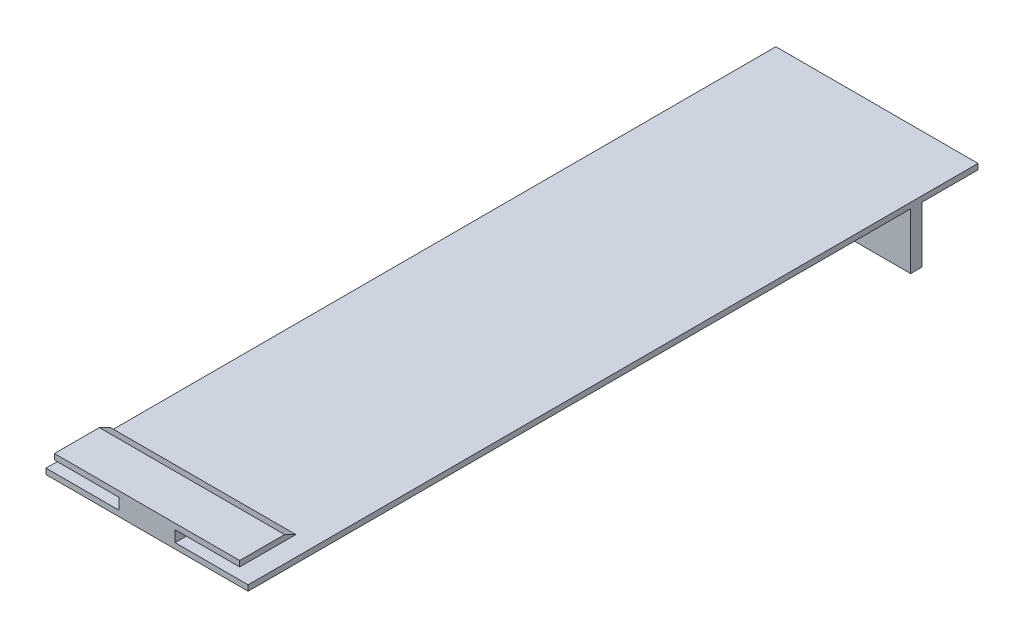
SolidWorks part; units mm, degrees
ref_plane "Front Plane" through (0, 0, 0) normal (0, 0, 1) x (1, 0, 0)
ref_plane "Top Plane" through (0, 0, 0) normal (0, 1, 0) x (1, 0, 0)
ref_plane "Right Plane" through (0, 0, 0) normal (1, 0, 0) x (0, 0, -1)
sketch "Sketch1" plane through (0, 0, 0) normal (0, 0, 1) x (1, 0, 0)
  line L1 (-18, -0.5) -> (18, -0.5)
  line L2 (-18, -0.5) -> (-18, 0.5)
  line L3 (-18, 0.5) -> (18, 0.5)
  line L4 (18, -0.5) -> (18, 0.5)
  line L5 (-18, -0.5) -> (18, 0.5) construction
  line L6 (-18, 0.5) -> (18, -0.5) construction
  point P0 (0, 0)
  dimension "D1" = 1
  dimension "D2" = 36
extrude "Boss-Extrude1" add sketch "Sketch1" along normal mid plane 130
ref_plane "Plane1" through (0, 0, 60) normal (0, 0, 1) x (1, 0, 0)
sketch "Sketch2" plane through (0, 0, 60) normal (0, 0, 1) x (1, 0, 0)
  line L0 (-5, 0.5) -> (-5, 2.5)
  line L1 (18, 0.5) -> (-18, 0.5) construction
  line L2 (-5, 2.5) -> (-16.5, 2.5)
  line L3 (-16.5, 2.5) -> (-16.5, 3.5)
  line L4 (-16.5, 3.5) -> (16.5, 3.5)
  line L5 (16.5, 3.5) -> (16.5, 2.5)
  line L6 (16.5, 2.5) -> (5, 2.5)
  line L7 (5, 2.5) -> (5, 0.5)
  line L8 (5, 0.5) -> (-5, 0.5)
  line L9 (0, 0) -> (0, 9.7402) construction
  dimension "D1" = 3
  dimension "D2" = 2
  dimension "D3" = 10
  dimension "D4" = 33
extrude "Boss-Extrude2" add sketch "Sketch2" along normal mid plane 10
sketch "Sketch3" plane through (0, -0.5, 0) normal (0, -1, 0) x (1, 0, 0)
  line L0 (18, 65) -> (18, -65) construction
  line L1 (-18, -55) -> (18, -55)
  line L2 (-18, -55) -> (-18, -53)
  line L3 (-18, -53) -> (18, -53)
  line L4 (18, -55) -> (18, -53)
  line L5 (-18, -55) -> (18, -53) construction
  line L6 (-18, -53) -> (18, -55) construction
  line L7 (-18, -65) -> (18, -65) construction
  line L8 (-18, 65) -> (-18, -65) construction
  point P0 (0, -54)
  dimension "D1" = 2
  dimension "D2" = 10
extrude "Boss-Extrude3" add sketch "Sketch3" along normal blind 10
sketch "Sketch4" plane through (16.5, 0, 0) normal (1, 0, 0) x (0, 0, -1)
  line L0 (-57, 3.5) -> (-55, 2.5)
  line L1 (-65, 3.5) -> (-55, 3.5) construction
  line L2 (-55, 2.5) -> (-55, 3.5)
  line L3 (-55, 3.5) -> (-57, 3.5)
  dimension "D1" = 2
extrude "Cut-Extrude1" cut sketch "Sketch4" against normal up to next
